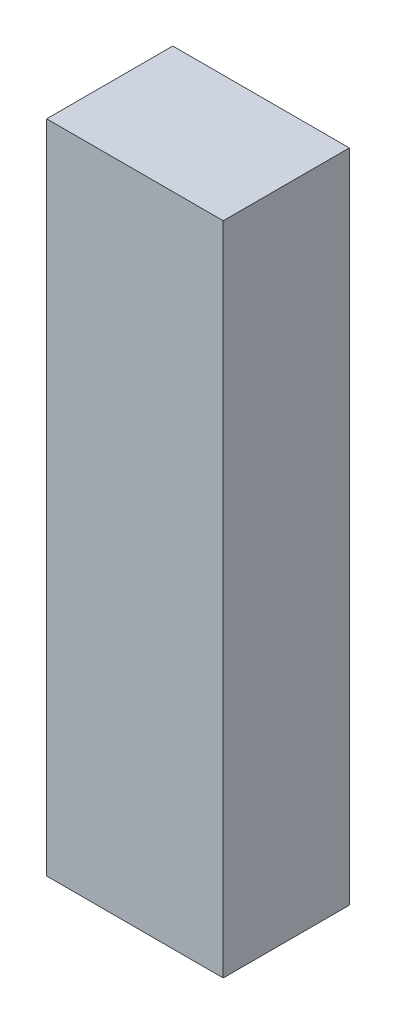
SolidWorks part; units mm, degrees
ref_plane "前视基准面" through (0, 0, 0) normal (0, 0, 1) x (1, 0, 0)
ref_plane "上视基准面" through (0, 0, 0) normal (0, 1, 0) x (1, 0, 0)
ref_plane "右视基准面" through (0, 0, 0) normal (1, 0, 0) x (0, 0, -1)
other "Configuration Table"
sketch "草图1" plane through (0, 0, 0) normal (0, 0, 1) x (1, 0, 0)
  line L1 (-7, -26) -> (7, -26)
  line L2 (-7, -26) -> (-7, 26)
  line L3 (-7, 26) -> (7, 26)
  line L4 (7, -26) -> (7, 26)
extrude "凸台-拉伸1" add sketch "草图1" against normal blind 10
